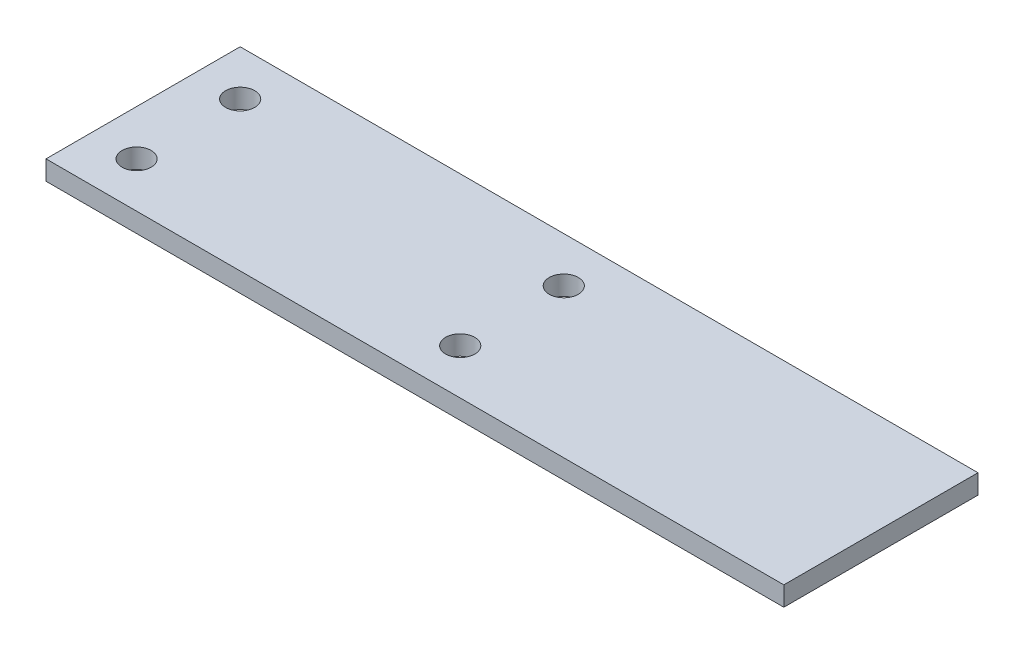
SolidWorks part; units mm, degrees
ref_plane "Front Plane" through (0, 0, 0) normal (0, 0, 1) x (1, 0, 0)
ref_plane "Top Plane" through (0, 0, 0) normal (0, 1, 0) x (1, 0, 0)
ref_plane "Right Plane" through (0, 0, 0) normal (1, 0, 0) x (0, 0, -1)
sketch "Sketch1" plane through (0, 0, 0) normal (0, 1, 0) x (1, 0, 0)
  line L0 (0, 16) -> (0, 0) construction
  line L1 (0, 0) -> (50, 0) construction
  line L2 (0, 16) -> (50, 16) construction
  line L3 (-7, 23) -> (-7, -7)
  line L4 (-7, 23) -> (57, 23)
  line L6 (57, -7) -> (-7, -7)
  line L7 (57, 23) -> (107, 23)
  line L8 (107, 23) -> (107, -7)
  line L9 (107, -7) -> (57, -7)
  circle A0 centre (0, 0) radius 2.25
  circle A1 centre (0, 16) radius 2.25
  circle A2 centre (50, 0) radius 2.25
  circle A3 centre (50, 16) radius 2.25
  point P11 (-7, 8)
  point P12 (0, 8)
  dimension "D1" = 4.5
  dimension "D2" = 16
  dimension "D3" = 50
  dimension "D4" = 30
  dimension "D5" = 7
  dimension "D7" = 50
extrude "Boss-Extrude1" add sketch "Sketch1" along normal blind 3
